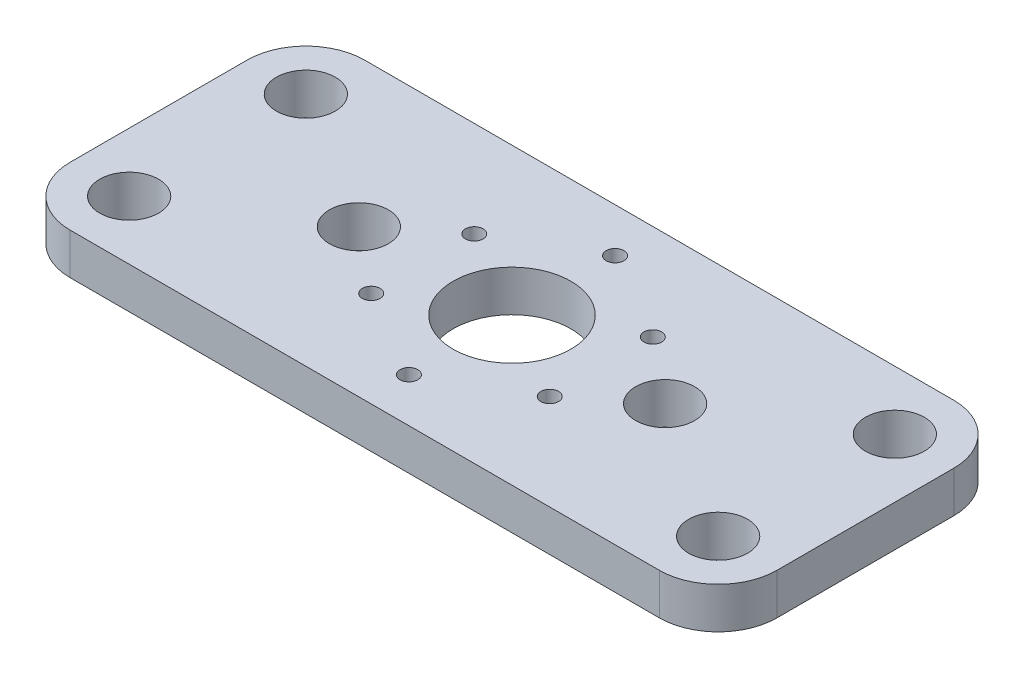
SolidWorks part; units mm, degrees
ref_plane "Front Plane" through (0, 0, 0) normal (0, 0, 1) x (1, 0, 0)
ref_plane "Top Plane" through (0, 0, 0) normal (0, 1, 0) x (1, 0, 0)
ref_plane "Right Plane" through (0, 0, 0) normal (1, 0, 0) x (0, 0, -1)
sketch "Sketch1" plane through (0, 0, 0) normal (0, 1, 0) x (1, 0, 0)
  line L0 (0, -1000) -> (0, 49000) construction
  line L1 (-50, -25) -> (50, -25)
  line L2 (-60, -15) -> (-60, 15)
  line L3 (-50, 25) -> (50, 25)
  line L4 (60, -15) -> (60, 15)
  line L5 (-61.0832, -24.9221) -> (59.2838, 24.188) construction
  line L6 (-60, 25) -> (60, -25) construction
  line L7 (-1000, 0) -> (49000, 0) construction
  arc A0 (50, -25) -> (60, -15) centre (50, -15) ccw
  arc A1 (-60, 15) -> (-50, 25) centre (-50, 15) cw
  circle A2 centre (0, 0) radius 10
  circle A4 centre (0, 17.5) radius 1.5
  circle A5 centre (-26, 0) radius 5
  circle A6 centre (26, 0) radius 5
  circle A7 centre (-50, 15) radius 5
  circle A8 centre (-50, -15) radius 5
  circle A9 centre (50, -15) radius 5
  circle A10 centre (50, 15) radius 5
  arc A11 (50, 25) -> (60, 15) centre (50, 15) cw
  arc A12 (-50, -25) -> (-60, -15) centre (-50, -15) cw
  circle A13 centre (15.1554, 8.75) radius 1.5
  circle A14 centre (15.1554, -8.75) radius 1.5
  circle A15 centre (0, -17.5) radius 1.5
  circle A16 centre (-15.1554, -8.75) radius 1.5
  circle A17 centre (-15.1554, 8.75) radius 1.5
  point P0 (0, 0)
  point P14 (0, 0)
  point P44 (0, 0)
  point P45 (0, 0)
  point P49 (0, 0)
  point P50 (0, 0)
  dimension "D1" = 10
  dimension "D5" = 20
  dimension "D6" = 35
  dimension "D7" = 3
  dimension "D8" = 10
  dimension "D12" = 30
  dimension "D14" = 10
  dimension "D10" = 30
  dimension "D18" = 17.5
  dimension "D2" = 120
  dimension "D3" = 50
  dimension "D4" = 25
  dimension "D9" = 26
  dimension "D11" = 52
  dimension "D13" = 10
  dimension "D15" = 60
  dimension "D16" = 60
  dimension "D17" = 6
extrude "Boss-Extrude1" add sketch "Sketch1" along normal blind 7
